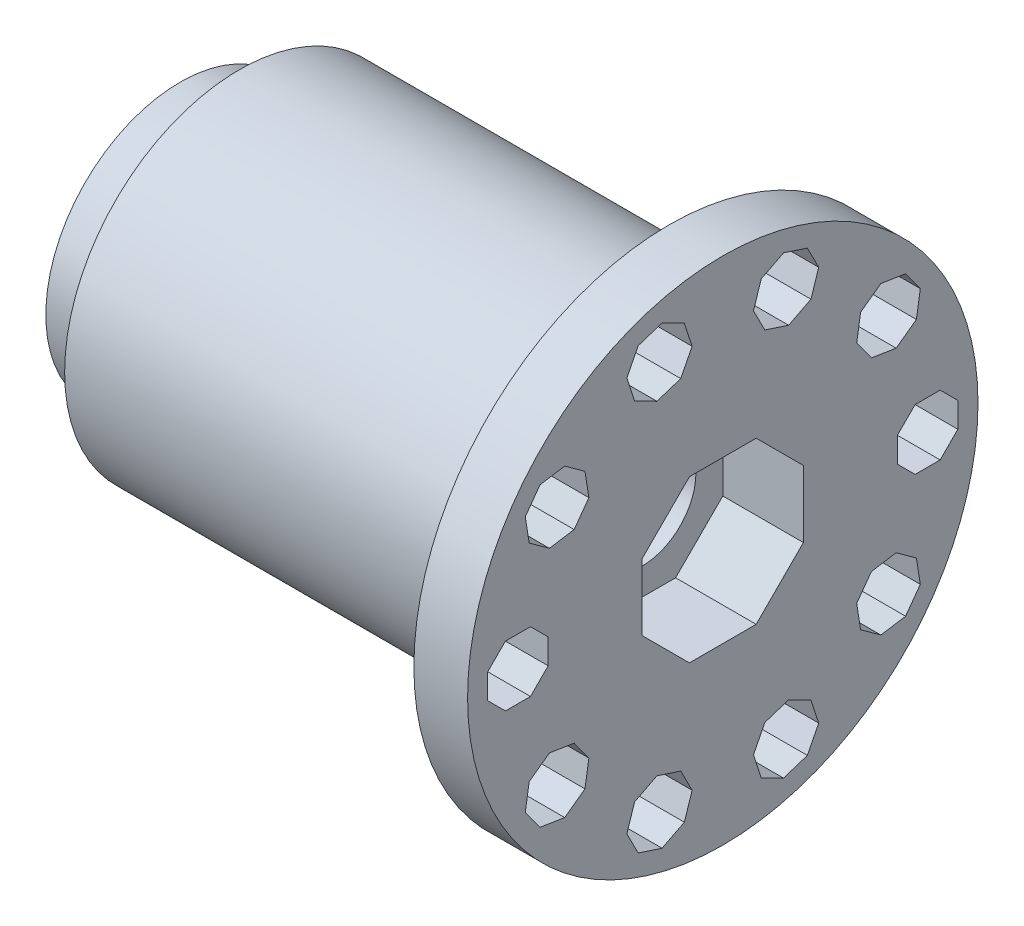
SolidWorks part; units mm, degrees
ref_plane "Alzado" through (0, 0, 0) normal (1, 0, 0) x (0, 1, 0)
ref_plane "Planta" through (0, 0, 0) normal (0, 0, 1) x (0, 1, 0)
ref_plane "Vista lateral" through (0, 0, 0) normal (0, 1, 0) x (-1, 0, 0)
sketch "Croquis1" plane through (0, 0, 0) normal (0, 0, 1) x (0, 1, 0)
  line L0 (0, 0) -> (0, 40.4) construction
  line L1 (0, 0) -> (19, 0)
  line L2 (19, 0) -> (19, 4)
  line L3 (19, 4) -> (13, 4)
  line L4 (13, 4) -> (13, 36)
  line L5 (13, 36) -> (10, 36)
  line L6 (10, 36) -> (10, 40.4)
  line L7 (10, 40.4) -> (0, 40.4)
  line L8 (0, 0) -> (0, 40.4)
  point P3 (11.5, 36)
  dimension "D1" = 40.4
  dimension "D2" = 4
  dimension "D3" = 38
  dimension "D4" = 26
  dimension "D5" = 20
  dimension "D6" = 4.4
revolve "Revolución1" add sketch "Croquis1" angle 360 about L0
sketch "Croquis2" plane through (0, 0, 0) normal (1, 0, 0) x (0, 1, 0)
  line L0 (0, 0) -> (13.7687, 0) construction
  line L8 (2.4853, -6) -> (6, -2.4853)
  line L9 (6, -2.4853) -> (6, 2.4853)
  line L10 (6, 2.4853) -> (2.4853, 6)
  line L11 (2.4853, 6) -> (-2.4853, 6)
  line L12 (-2.4853, 6) -> (-6, 2.4853)
  line L13 (-6, 2.4853) -> (-6, -2.4853)
  line L14 (-6, -2.4853) -> (-2.4853, -6)
  line L15 (-2.4853, -6) -> (2.4853, -6)
  circle A0 centre (0, 0) radius 6 construction
  dimension "D1" = 12
extrude "Cortar-Extruir1" cut sketch "Croquis2" against normal blind 6
ref_plane "Plano1" through (-20.2, 0, 0) normal (1, 0, 0) x (0, 0, -1)
mirror "Simetría1" about plane through (-20.2, 0, 0) normal (1, 0, 0) of "Cortar-Extruir1"
sketch "Croquis3" plane through (0, 0, 0) normal (1, 0, 0) x (0, 1, 0)
  line L0 (0, 0) -> (0, 19) construction
  line L1 (0, 0) -> (19, 0) construction
  line L3 (2.25, 14.318) -> (2.25, 16.182)
  line L4 (2.25, 16.182) -> (0.932, 17.5)
  line L5 (0.932, 17.5) -> (-0.932, 17.5)
  line L6 (-0.932, 17.5) -> (-2.25, 16.182)
  line L7 (-2.25, 16.182) -> (-2.25, 14.318)
  line L8 (-2.25, 14.318) -> (-0.932, 13)
  line L9 (-0.932, 13) -> (0.932, 13)
  line L10 (0.932, 13) -> (2.25, 14.318)
  circle A0 centre (0, 0) radius 19 construction
  circle A1 centre (0, 15.25) radius 2.25 construction
  circle A2 centre (0, 0) radius 13 construction
  dimension "D3" = 26
  dimension "D1" = 4.5
extrude "Cortar-Extruir2" cut sketch "Croquis3" against normal up to surface (4 mm away) up to face at (-4, 0, -13)
pattern_circular "MatrizC1" count 10 over 360 about axis through (0, 0, 0) along (1, 0, 0) of "Cortar-Extruir2"
sketch "Croquis4" plane through (-6, 0, 0) normal (1, 0, 0) x (0, 1, 0)
  circle A0 centre (0, 0) radius 4
  dimension "D1" = 8
extrude "Cortar-Extruir3" cut sketch "Croquis4" against normal through all
